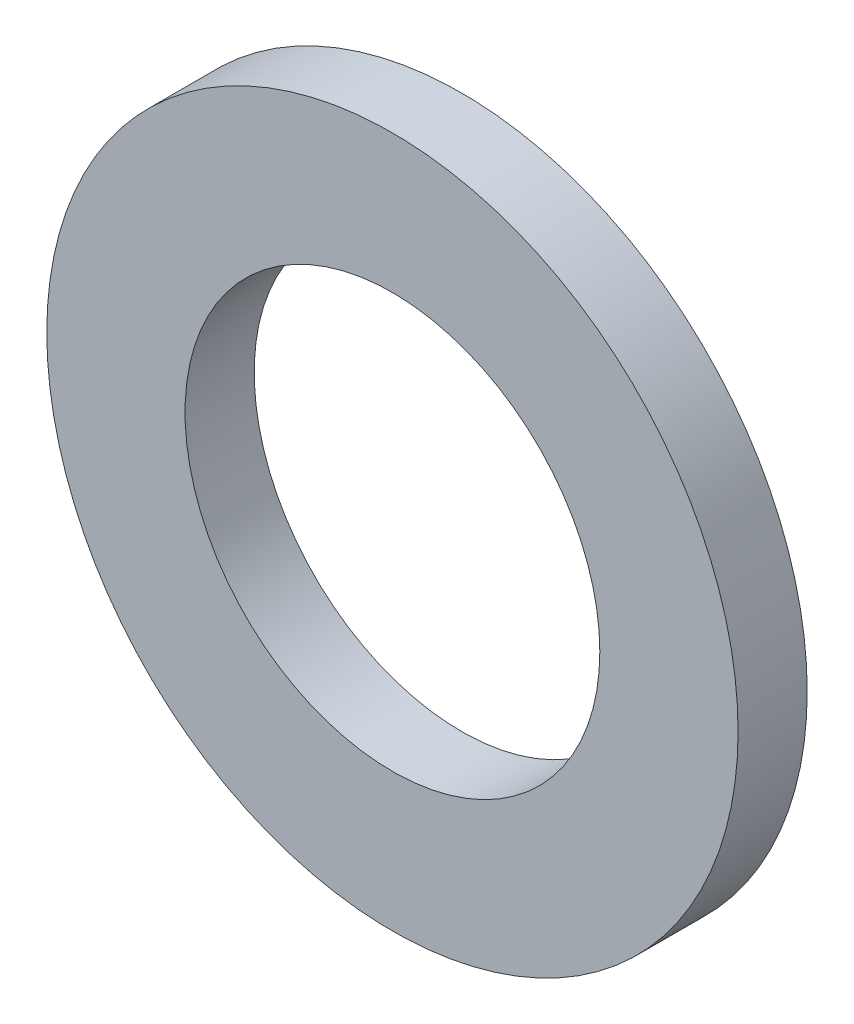
SolidWorks part; units mm, degrees
material "POM Acetal Copolymer"
ref_plane "Front Plane" through (0, 0, 0) normal (0, 0, 1) x (1, 0, 0)
ref_plane "Top Plane" through (0, 0, 0) normal (0, 1, 0) x (1, 0, 0)
ref_plane "Right Plane" through (0, 0, 0) normal (1, 0, 0) x (0, 0, -1)
sketch "Sketch1" plane through (0, 0, 0) normal (0, 0, 1) x (1, 0, 0)
  circle A0 centre (0, 0) radius 2.4
  circle A1 centre (0, 0) radius 4
  dimension "D1" = 4.8
  dimension "D2" = 8
extrude "Boss-Extrude1" add sketch "Sketch1" along normal blind 0.8
